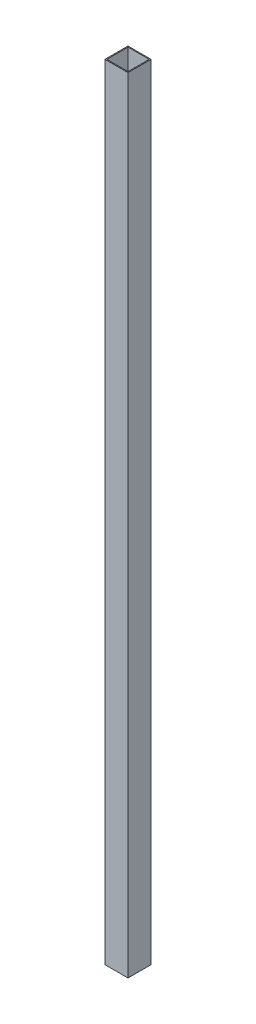
SolidWorks part; units mm, degrees
ref_plane "Front Plane" through (0, 0, 0) normal (0, 0, 1) x (1, 0, 0)
ref_plane "Top Plane" through (0, 0, 0) normal (0, 1, 0) x (1, 0, 0)
ref_plane "Right Plane" through (0, 0, 0) normal (1, 0, 0) x (0, 0, -1)
sketch "Sketch1" plane through (0, 0, 0) normal (0, 1, 0) x (1, 0, 0)
  line L0 (-23, 23) -> (23, 23)
  line L1 (-25, -25) -> (25, -25)
  line L2 (-25, -25) -> (-25, 25)
  line L3 (-25, 25) -> (25, 25)
  line L4 (25, -25) -> (25, 25)
  line L5 (-25, -25) -> (25, 25) construction
  line L6 (-25, 25) -> (25, -25) construction
  line L7 (23, -23) -> (23, 23)
  line L8 (-23, -23) -> (23, -23)
  line L9 (-23, -23) -> (-23, 23)
  point P0 (0, 0)
  dimension "D1" = 50
  dimension "D2" = 2
extrude "Boss-Extrude1" add sketch "Sketch1" along normal blind 1700
